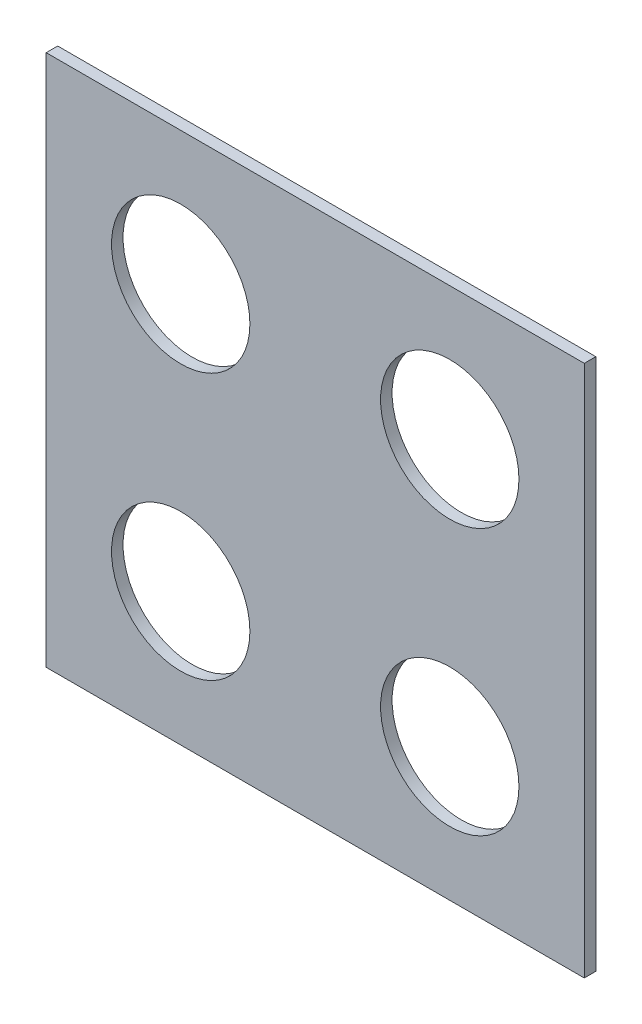
SolidWorks part; units mm, degrees
material "Acrylic (Medium-high impact)"
ref_plane "Front Plane" through (0, 0, 0) normal (0, 0, 1) x (1, 0, 0)
ref_plane "Top Plane" through (0, 0, 0) normal (0, 1, 0) x (1, 0, 0)
ref_plane "Right Plane" through (0, 0, 0) normal (1, 0, 0) x (0, 0, -1)
sketch "Sketch1" plane through (0, 0, 0) normal (0, 0, 1) x (1, 0, 0)
  line L1 (140, -138.5) -> (-140, -138.5)
  line L2 (140, -138.5) -> (140, 138.5)
  line L3 (140, 138.5) -> (-140, 138.5)
  line L4 (-140, -138.5) -> (-140, 138.5)
  line L5 (140, -138.5) -> (-140, 138.5) construction
  line L6 (140, 138.5) -> (-140, -138.5) construction
  point P0 (0, 0)
  dimension "D1" = 277
  dimension "D2" = 280
extrude "Boss-Extrude1" add sketch "Sketch1" along normal blind 6
sketch "Sketch2" plane through (0, 0, 6) normal (0, 0, 1) x (1, 0, 0)
  line L0 (0, 138.5) -> (140, 0) construction
  line L1 (-140, 0) -> (0, -138.5) construction
  line L2 (-140, 0) -> (0, 138.5) construction
  line L3 (-140, 138.5) -> (-140, -138.5) construction
  line L4 (140, 138.5) -> (-140, 138.5) construction
  line L6 (140, -138.5) -> (140, 138.5) construction
  line L7 (140, 0) -> (0, -138.5) construction
  line L8 (-140, -138.5) -> (140, -138.5) construction
  circle A0 centre (-70, 69.25) radius 36
  circle A1 centre (-70, -69.25) radius 36
  circle A2 centre (70, -69.25) radius 36
  circle A3 centre (70, 69.25) radius 36
  dimension "D1" = 72
  dimension "D2" = 72
  dimension "D3" = 72
  dimension "D4" = 72
extrude "Cut-Extrude1" cut sketch "Sketch2" against normal through all
